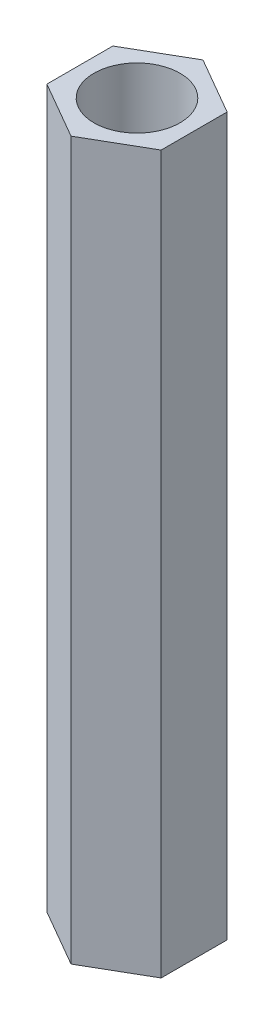
SolidWorks part; units mm, degrees
material "黄铜"
ref_plane "前视基准面" through (0, 0, 0) normal (0, 0, 1) x (1, 0, 0)
ref_plane "上视基准面" through (0, 0, 0) normal (0, 1, 0) x (1, 0, 0)
ref_plane "右视基准面" through (0, 0, 0) normal (1, 0, 0) x (0, 0, -1)
other "Configuration Table"
sketch "草图1" plane through (0, 0, 0) normal (0, 1, 0) x (1, 0, 0)
  line L1 (0, 2.3) -> (-1.9919, 1.15)
  line L2 (-1.9919, 1.15) -> (-1.9919, -1.15)
  line L3 (-1.9919, -1.15) -> (0, -2.3)
  line L4 (0, -2.3) -> (1.9919, -1.15)
  line L5 (1.9919, -1.15) -> (1.9919, 1.15)
  line L6 (1.9919, 1.15) -> (0, 2.3)
  circle A0 centre (0, 0) radius 1.5
  circle A1 centre (0, 0) radius 1.9919 construction
  dimension "D1" = 3
  dimension "D2" = 4.6
extrude "凸台-拉伸1" add sketch "草图1" along normal blind 25
